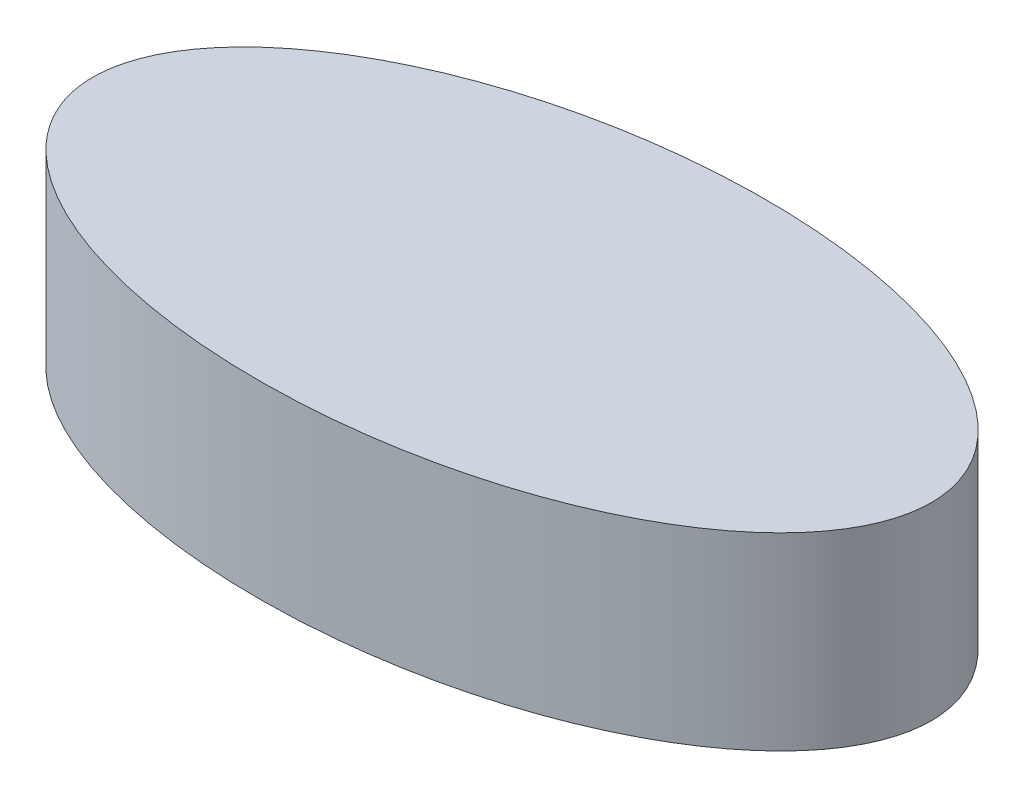
SolidWorks part; units mm, degrees
ref_plane "Alzado" through (0, 0, 0) normal (0, 0, 1) x (1, 0, 0)
ref_plane "Planta" through (0, 0, 0) normal (0, 1, 0) x (1, 0, 0)
ref_plane "Vista lateral" through (0, 0, 0) normal (1, 0, 0) x (0, 0, -1)
sketch "Croquis1" plane through (0, 0, 0) normal (0, 1, 0) x (1, 0, 0)
  ellipse E0 centre (0, 0) end of major axis (87.4555, 7.7099) minor radius 45.1033
extrude "Saliente-Extruir1" add sketch "Croquis1" along normal blind 42
